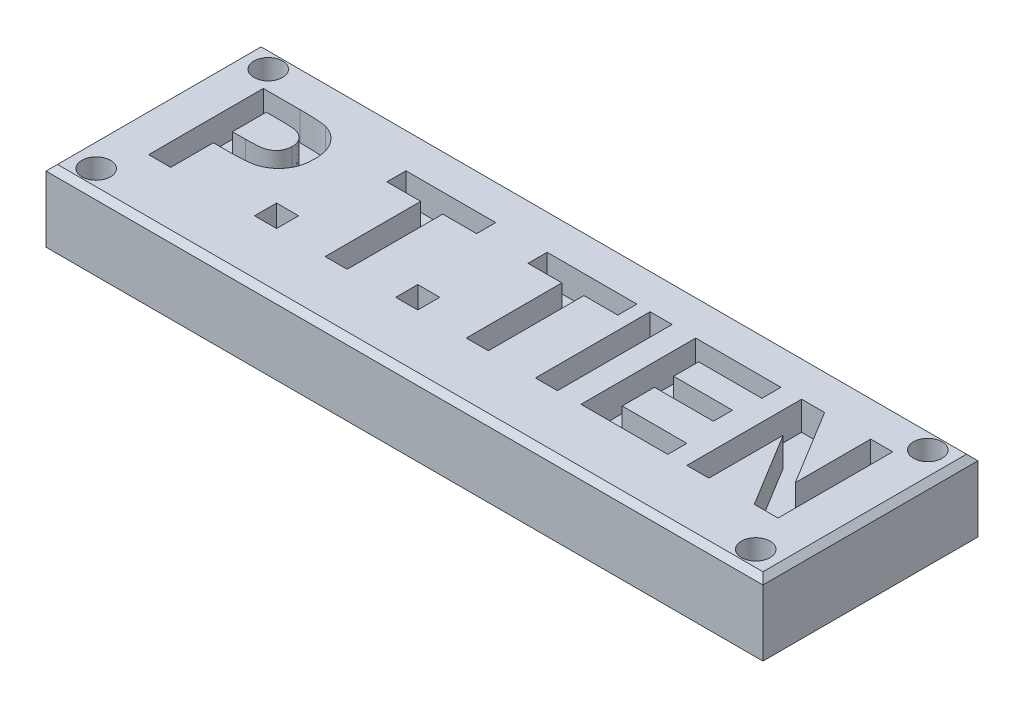
SolidWorks part; units mm, degrees
ref_plane "Front Plane" through (0, 0, 0) normal (0, 0, 1) x (1, 0, 0)
ref_plane "Top Plane" through (0, 0, 0) normal (0, 1, 0) x (1, 0, 0)
ref_plane "Right Plane" through (0, 0, 0) normal (1, 0, 0) x (0, 0, -1)
sketch "Sketch1" plane through (0, 0, 0) normal (0, 1, 0) x (1, 0, 0)
  line L1 (-250, 75) -> (250, 75)
  line L2 (-250, 75) -> (-250, -75)
  line L3 (-250, -75) -> (250, -75)
  line L4 (250, 75) -> (250, -75)
  line L5 (-250, 75) -> (250, -75) construction
  line L6 (-250, -75) -> (250, 75) construction
  point P0 (0, 0)
  dimension "D1" = 500
  dimension "D2" = 150
extrude "Boss-Extrude1" add sketch "Sketch1" along normal blind 50
sketch "Sketch2" plane through (0, 50, 0) normal (0, 1, 0) x (1, 0, 0)
  text T0 "P.T.TIEN" font "Arial" height 80
extrude "Cut-Extrude1" cut sketch "Sketch2" against normal blind 20
sketch "Sketch3" plane through (0, 50, 0) normal (0, 1, 0) x (1, 0, 0)
  line L1 (230, 60) -> (-230, 60) construction
  line L2 (230, 60) -> (230, -60) construction
  line L3 (230, -60) -> (-230, -60) construction
  line L4 (-230, 60) -> (-230, -60) construction
  line L5 (230, 60) -> (-230, -60) construction
  line L6 (230, -60) -> (-230, 60) construction
  circle A0 centre (-230, 60) radius 10
  circle A1 centre (-230, -60) radius 10
  circle A2 centre (230, -60) radius 10
  circle A3 centre (230, 60) radius 10
  point P0 (0, 0)
  dimension "D3" = 20
  dimension "D1" = 120
  dimension "D2" = 460
extrude "Cut-Extrude2" cut sketch "Sketch3" against normal through all
chamfer "Chamfer1" distance 4 angle 45 4 edges at (-250, 50, 0) (0, 50, -75) (250, 50, 0) (0, 50, 75)
